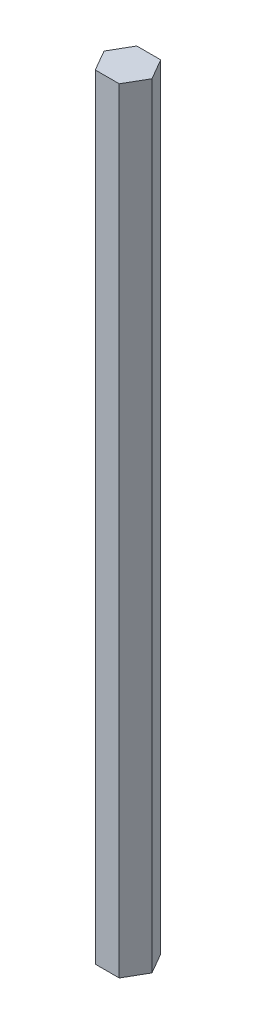
SolidWorks part; units mm, degrees
ref_plane "Front Plane" through (0, 0, 0) normal (0, 0, 1) x (1, 0, 0)
ref_plane "Top Plane" through (0, 0, 0) normal (0, 1, 0) x (1, 0, 0)
ref_plane "Right Plane" through (0, 0, 0) normal (1, 0, 0) x (0, 0, -1)
sketch "Sketch1" plane through (0, 0, 0) normal (0, 1, 0) x (1, 0, 0)
  line L1 (3, 0) -> (1.5, 2.5981)
  line L2 (1.5, 2.5981) -> (-1.5, 2.5981)
  line L3 (-1.5, 2.5981) -> (-3, 0)
  line L4 (-3, 0) -> (-1.5, -2.5981)
  line L5 (-1.5, -2.5981) -> (1.5, -2.5981)
  line L6 (1.5, -2.5981) -> (3, 0)
  circle A0 centre (0, 0) radius 2.5981 construction
  dimension "D1" = 3
extrude "Boss-Extrude1" add sketch "Sketch1" along normal blind 97
sketch "Sketch3" plane through (0, 0, 0) normal (0, -1, 0) x (1, 0, 0)
  circle A0 centre (0, 0) radius 1.6
  dimension "D1" = 3.2
extrude "Cut-Extrude1" cut sketch "Sketch3" against normal blind 5
